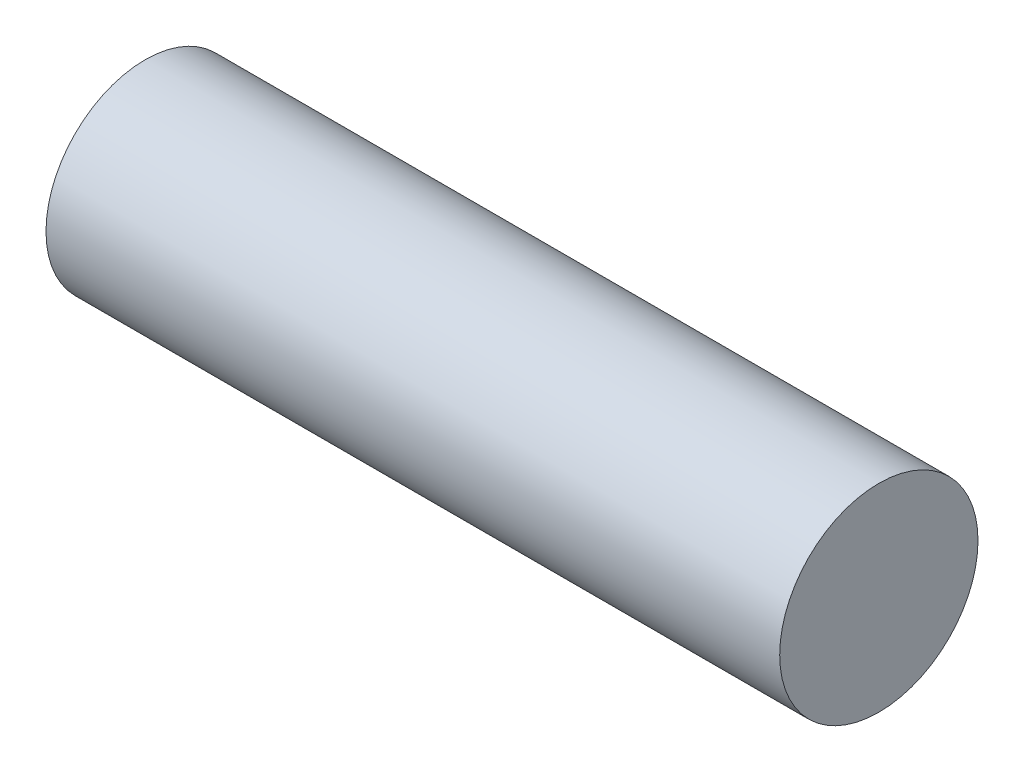
SolidWorks part; units mm, degrees
ref_plane "정면" through (0, 0, 0) normal (0, 0, 1) x (1, 0, 0)
ref_plane "윗면" through (0, 0, 0) normal (0, 1, 0) x (1, 0, 0)
ref_plane "우측면" through (0, 0, 0) normal (1, 0, 0) x (0, 0, -1)
sketch "Sketch1" plane through (0, 0, 0) normal (1, 0, 0) x (0, 0, -1)
  circle A0 centre (0, 0) radius 5
  dimension "D1" = 10
extrude "Boss-Extrude1" add sketch "Sketch1" along normal mid plane 37
